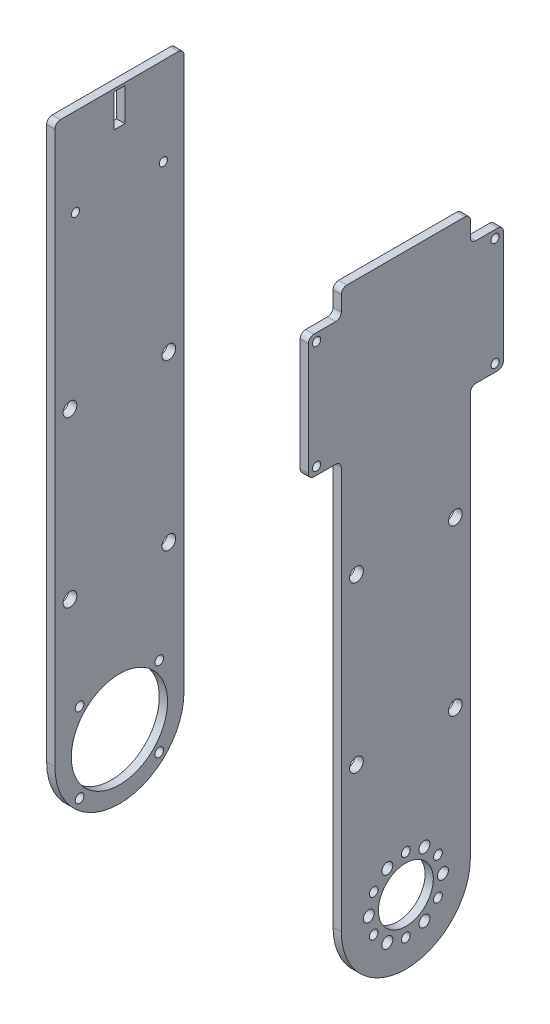
SolidWorks part; units mm, degrees
material "A-玻璃纤维"
ref_plane "前视基准面" through (0, 0, 0) normal (0, 0, 1) x (1, 0, 0)
ref_plane "上视基准面" through (0, 0, 0) normal (0, 1, 0) x (1, 0, 0)
ref_plane "右视基准面" through (0, 0, 0) normal (1, 0, 0) x (0, 0, -1)
other "Configuration Table"
sketch "草图1" plane through (0, 0, 0) normal (0, 1, 0) x (1, 0, 0)
  line L1 (-50.65, -23.5) -> (50.65, -23.5)
  line L2 (-50.65, -23.5) -> (-50.65, 23.5)
  line L3 (-50.65, 23.5) -> (50.65, 23.5)
  line L4 (50.65, -23.5) -> (50.65, 23.5)
  line L5 (-50.65, -23.5) -> (50.65, 23.5) construction
  line L6 (-50.65, 23.5) -> (50.65, -23.5) construction
  point P0 (0, 0)
  dimension "D1" = 101.3
  dimension "D2" = 47
extrude "凸台-拉伸1" add sketch "草图1" along normal blind 3
sketch "草图2" plane through (-50.65, 0, 0) normal (-1, 0, 0) x (0, 0, 1)
  line L0 (-23.5, 0) -> (23.5, 0) construction
  line L1 (-23.5, 0) -> (-23.5, -200)
  line L2 (-23.5, 0) -> (-23.5, 3)
  line L3 (-23.5, 3) -> (23.5, 3)
  line L4 (23.5, 3) -> (23.5, 0)
  line L5 (23.5, 0) -> (23.5, -200)
  circle A0 centre (0, -200) radius 23.5
  line M1 (-23.5, 0) -> (23.5, 0)
  line M2 (23.5, 0) -> (23.5, 3)
  line M3 (23.5, 3) -> (-23.5, 3)
  line M4 (-23.5, 3) -> (-23.5, 0)
  dimension "D1" = 47
  dimension "D2" = 200
extrude "凸台-拉伸2" add sketch "草图2" along normal blind 3 contours A0 L5 L1 M1 | M4 M1 M2 M3 | A0
sketch "草图3" plane through (50.65, 0, 0) normal (1, 0, 0) x (0, 0, -1)
  line L0 (-23.5, 0) -> (-23.5, -200)
  line L1 (-23.5, 0) -> (-23.5, 3)
  line L2 (-23.5, 3) -> (23.5, 3)
  line L3 (23.5, 3) -> (23.5, 0)
  line L4 (23.5, 0) -> (23.5, -200)
  circle A0 centre (0, -200) radius 23.5
  line M1 (-23.5, 0) -> (23.5, 0)
  line M2 (23.5, 0) -> (23.5, 3)
  line M3 (23.5, 3) -> (-23.5, 3)
  line M4 (-23.5, 3) -> (-23.5, 0)
  dimension "D1" = 47
extrude "凸台-拉伸3" add sketch "草图3" along normal blind 3 contours A0 L4 L0 M1 | M4 M1 M2 M3 | A0
sketch "草图5" plane through (0, 3, 0) normal (0, 1, 0) x (1, 0, 0)
  line L0 (0, 0) -> (21.6506, -12.5) construction
  circle A0 centre (0, 0) radius 25 construction
  circle A1 centre (21.6506, -12.5) radius 2
  circle A2 centre (0, -25) radius 2
  circle A3 centre (-21.6506, -12.5) radius 2
  circle A4 centre (-21.6506, 12.5) radius 2
  circle A5 centre (0, 25) radius 2
  circle A6 centre (21.6506, 12.5) radius 2
  dimension "D1" = 50
  dimension "D2" = 4
  dimension "D4" = 25
  dimension "D3" = 6
extrude "切除-拉伸2" cut sketch "草图5" against normal blind 3
sketch "草图6" plane through (0, 3, 0) normal (0, 1, 0) x (1, 0, 0)
  line L0 (0, -25) -> (0, 25) construction
  line L1 (-6.4705, 24.1481) -> (6.4705, -24.1481) construction
  circle A0 centre (0, 0) radius 25 construction
  circle A1 centre (-6.4705, 24.1481) radius 1.5
  circle A2 centre (6.4705, -24.1481) radius 1.5
  circle A3 centre (-6.4705, -24.1481) radius 1.5
  circle A4 centre (6.4705, 24.1481) radius 1.5
  dimension "D2" = 3
  dimension "D3" = 3
  dimension "D1" = 15
extrude "切除-拉伸3" cut sketch "草图6" against normal blind 3
sketch "草图7" plane through (-53.65, 0, 0) normal (-1, 0, 0) x (0, 0, 1)
  line L0 (0, -200) -> (14.4957, -185.5043) construction
  circle A0 centre (0, -200) radius 17.52
  circle A1 centre (0, -200) radius 20.5 construction
  circle A2 centre (14.4957, -185.5043) radius 1.6
  circle A3 centre (14.4957, -214.4957) radius 1.6
  circle A4 centre (-14.4957, -214.4957) radius 1.6
  circle A5 centre (-14.4957, -185.5043) radius 1.6
  dimension "D1" = 35.04
  dimension "D2" = 41
  dimension "D3" = 3.2
  dimension "D4" = 4
extrude "切除-拉伸4" cut sketch "草图7" against normal blind 3
sketch "草图8" plane through (53.65, 0, 0) normal (1, 0, 0) x (0, 0, -1)
  line L0 (0, -200) -> (0, -213.5) construction
  line L1 (0, -200) -> (13.5, -200) construction
  circle A0 centre (0, -200) radius 10
  circle A1 centre (0, -200) radius 13.5 construction
  circle A2 centre (0, -213.5) radius 1.6
  circle A3 centre (-11.6913, -206.75) radius 1.6
  circle A4 centre (-11.6913, -193.25) radius 1.6
  circle A5 centre (0, -186.5) radius 1.6
  circle A6 centre (11.6913, -193.25) radius 1.6
  circle A7 centre (11.6913, -206.75) radius 1.6
  circle A8 centre (13.5, -200) radius 2
  circle A9 centre (6.75, -211.6913) radius 2
  circle A10 centre (-6.75, -211.6913) radius 2
  circle A11 centre (-13.5, -200) radius 2
  circle A12 centre (-6.75, -188.3087) radius 2
  circle A13 centre (6.75, -188.3087) radius 2
  dimension "D1" = 20
  dimension "D2" = 27
  dimension "D3" = 3.2
  dimension "D5" = 4
  dimension "D4" = 6
  dimension "D6" = 6
extrude "切除-拉伸5" cut sketch "草图8" against normal blind 3
sketch "草图15" plane through (0, 3, 0) normal (0, 1, 0) x (1, 0, 0)
  circle A0 centre (0, 0) radius 10
  dimension "D1" = 20
extrude "切除-拉伸10" cut sketch "草图15" against normal blind 10
sketch "草图16" plane through (0, 0, 0) normal (0, -1, 0) x (1, 0, 0)
  line L1 (-50.65, -23.5) -> (50.65, -23.5)
  line L2 (-50.65, -23.5) -> (-50.65, 23.5)
  line L3 (-50.65, 23.5) -> (50.65, 23.5)
  line L4 (50.65, -23.5) -> (50.65, 23.5)
  line L5 (-50.65, -23.5) -> (50.65, 23.5) construction
  line L6 (-50.65, 23.5) -> (50.65, -23.5) construction
  point P0 (0, 0)
extrude "切除-拉伸11" cut sketch "草图16" against normal blind 10
fillet "圆角1" radius 2 2 edges at (-52.15, 3, 23.5) (-52.15, 3, -23.5)
fillet "圆角2" radius 2 2 edges at (52.15, 3, -23.5) (52.15, 3, 23.5)
sketch "草图18" plane through (-53.65, 0, 0) normal (-1, 0, 0) x (0, 0, 1)
  line L0 (21.5, 3) -> (-21.5, 3) construction
  line L1 (-16, -29) -> (16, -29) construction
  line L2 (23.5, 1) -> (23.5, -200) construction
  line L3 (0, -4) -> (0, -29) construction
  line L4 (-2, -10) -> (2, -10)
  line L5 (-2, -10) -> (-2, 2)
  line L6 (-2, 2) -> (2, 2)
  line L7 (2, -10) -> (2, 2)
  line L8 (-2, -10) -> (2, 2) construction
  line L9 (-2, 2) -> (2, -10) construction
  line L11 (8.0154, -19.5875) -> (8.0154, -19.4002) construction
  circle A0 centre (-16, -29) radius 1.5
  circle A1 centre (16, -29) radius 1.5
  point P10 (0, -4)
  dimension "D1" = 3
  dimension "D2" = 32
  dimension "D3" = 32
  dimension "D4" = 7.5
  dimension "D6" = 12
  dimension "D7" = 4
  dimension "D8" = 1
extrude "切除-拉伸13" cut sketch "草图18" against normal blind 3
sketch "草图24" plane through (53.65, 0, 0) normal (1, 0, 0) x (0, 0, -1)
  line L0 (0, 3) -> (0, -223.5) construction
  line L1 (21.5, 3) -> (-21.5, 3) construction
  line L2 (-23.5, 1) -> (-23.5, -200) construction
  line L3 (-23.5, -6.5) -> (-35.5, -6.5)
  line L4 (-23.5, -6.5) -> (-23.5, -51.5)
  line L5 (-23.5, -51.5) -> (-35.5, -51.5)
  line L6 (-35.5, -6.5) -> (-35.5, -51.5)
  line L12 (-35.5, -29) -> (-23.5, -29) construction
  line L13 (23.5, -51.5) -> (35.5, -51.5)
  line L14 (35.5, -6.5) -> (35.5, -51.5)
  line L15 (23.5, -6.5) -> (35.5, -6.5)
  line L16 (23.5, -6.5) -> (23.5, -51.5)
  arc A0 (-23.5, -200) -> (23.5, -200) centre (0, -200) ccw construction
  dimension "D1" = 32
  dimension "D2" = 12
  dimension "D3" = 45
extrude "凸台-拉伸7" add sketch "草图24" against normal blind 3
sketch "草图25" plane through (53.65, 0, 0) normal (1, 0, 0) x (0, 0, -1)
  line L0 (-35.5, -29) -> (35.5, -29) construction
  line L1 (-35.5, -6.5) -> (-35.5, -51.5) construction
  line L2 (35.5, -51.5) -> (35.5, -6.5) construction
  line L3 (0, 3) -> (0, -29) construction
  line L4 (21.5, 3) -> (-21.5, 3) construction
  circle A0 centre (0, -29) radius 38 construction
  circle A1 centre (-32.5, -9.3086) radius 1.5
  circle A2 centre (-32.5, -48.6914) radius 1.5
  circle A3 centre (32.5, -9.3086) radius 1.5
  circle A4 centre (32.5, -48.6914) radius 1.5
  dimension "D1" = 76
  dimension "D3" = 3
  dimension "D2" = 32.5
extrude "切除-拉伸15" cut sketch "草图25" against normal through all
fillet "圆角4" radius 2 8 edges at (52.15, -6.5, 23.5) (52.15, -51.5, 23.5) (52.15, -51.5, 35.5) (52.15, -6.5, 35.5) (52.15, -51.5, -23.5) (52.15, -6.5, -23.5) (52.15, -6.5, -35.5) (52.15, -51.5, -35.5)
sketch "草图27" plane through (-53.65, 0, 0) normal (-1, 0, 0) x (0, 0, 1)
  line L0 (0, 3) -> (0, -223.5) construction
  line L1 (21.5, 3) -> (-21.5, 3) construction
  arc A0 (-23.5, -200) -> (23.5, -200) centre (0, -200) ccw construction
  circle A1 centre (-18, -150) radius 2.5
  circle A2 centre (0, -200) radius 17.52 construction
  circle A3 centre (-18, -90) radius 2.5
  circle A4 centre (18, -150) radius 2.5
  circle A5 centre (18, -90) radius 2.5
  point P13 (0, 0)
  point P14 (0, 0)
  dimension "D2" = 5
  dimension "D1" = 18
  dimension "D3" = 50
  dimension "D4" = 60
extrude "切除-拉伸16" cut sketch "草图27" against normal through all
